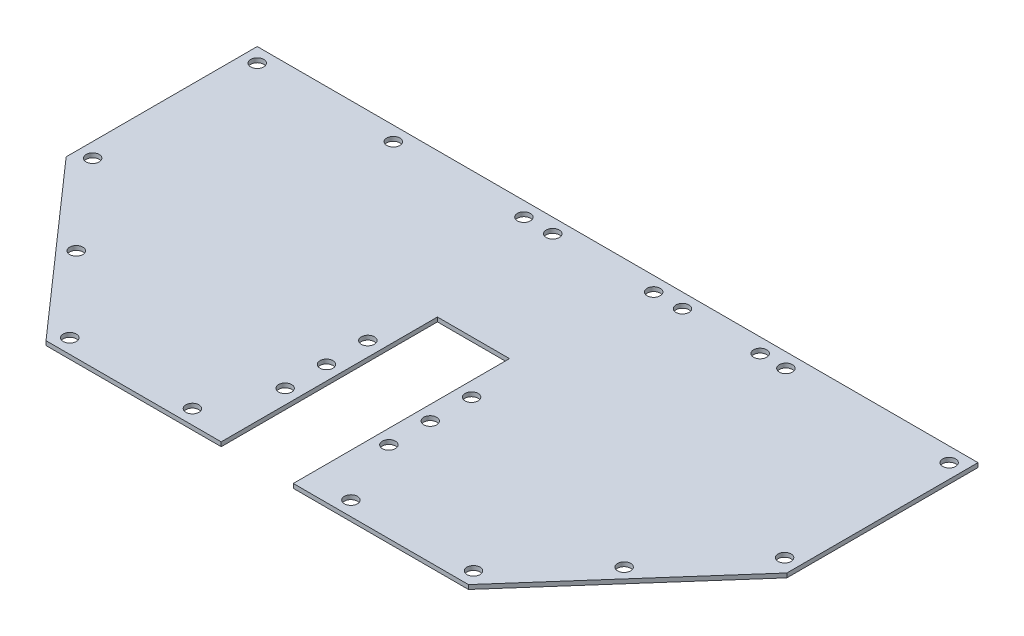
SolidWorks part; units mm, degrees
ref_plane "Front Plane" through (0, 0, 0) normal (0, 0, 1) x (1, 0, 0)
ref_plane "Top Plane" through (0, 0, 0) normal (0, 1, 0) x (1, 0, 0)
ref_plane "Right Plane" through (0, 0, 0) normal (1, 0, 0) x (0, 0, -1)
sketch "Sketch1" plane through (0, 0, 0) normal (0, 1, 0) x (1, 0, 0)
  line L1 (52.5563, -126.9959) -> (114.3, -126.9959)
  line L3 (254, 0) -> (0, 0)
  line L4 (0, 0) -> (0, -67.34)
  line L5 (0, -67.34) -> (52.5563, -126.9959)
  line L6 (254, 0) -> (254, -67.34)
  line L7 (254, -67.34) -> (201.4362, -126.9959)
  line L8 (114.3, -50.8) -> (139.7, -50.8)
  line L9 (139.7, -126.9959) -> (139.7, -50.8)
  line L10 (114.3, -126.9959) -> (114.3, -50.8)
  line L11 (139.7, -126.9959) -> (201.4362, -126.9959)
  circle A0 centre (5.08, -5.08) radius 2.3
  circle A1 centre (53.03, -5.08) radius 2.3
  circle A2 centre (99.06, -5.08) radius 2.3
  circle A3 centre (5.08, -63.08) radius 2.3
  circle A4 centre (99.0662, -121.9159) radius 2.3
  circle A5 centre (55.8562, -121.9159) radius 2.3
  circle A7 centre (182.3, -5.08) radius 2.3
  circle A8 centre (248.92, -5.0864) radius 2.3
  circle A9 centre (248.92, -63.0864) radius 2.3
  circle A10 centre (198.1362, -121.9159) radius 2.3
  circle A11 centre (154.9262, -121.9159) radius 2.3
  circle A13 centre (144.78, -5.08) radius 2.3
  circle A14 centre (109.22, -5.08) radius 2.3
  circle A15 centre (154.94, -5.08) radius 2.3
  circle A16 centre (191.38, -5.08) radius 2.3
  circle A17 centre (223.5281, -94.2391) radius 2.3
  circle A18 centre (144.78, -98.3859) radius 2.3
  circle A19 centre (144.78, -83.8159) radius 2.3
  circle A20 centre (144.78, -69.2459) radius 2.3
  circle A21 centre (109.22, -70.2459) radius 2.3
  circle A22 centre (109.22, -84.8159) radius 2.3
  circle A23 centre (109.22, -99.3859) radius 2.3
  circle A24 centre (30.4664, -94.2371) radius 2.3
  point P6 (52.5563, -126.9959)
  point P8 (201.4362, -126.9959)
  dimension "D3" = 5.08
  dimension "D6" = 47.95
  dimension "D7" = 46.03
  dimension "D8" = 58
  dimension "D9" = 5.08
  dimension "D13" = 43.21
  dimension "D14" = 5.08
  dimension "D15" = 4.6
  dimension "D16" = 4.6
  dimension "D17" = 4.6
  dimension "D18" = 5.08
  dimension "D19" = 4.6
  dimension "D20" = 4.6
  dimension "D21" = 4.6
  dimension "D1" = 67.34
  dimension "D2" = 254
  dimension "D4" = 5.08
  dimension "D5" = 67.34
  dimension "D10" = 22.53
  dimension "D11" = 25.4
  dimension "D12" = 114.3
  dimension "D22" = 10.16
  dimension "D23" = 35.56
  dimension "D24" = 10.16
  dimension "D25" = 27.36
  dimension "D26" = 9.08
  dimension "D27" = 57.54
  dimension "D28" = 58
  dimension "D29" = 5.08
  dimension "D30" = 5.08
  dimension "D31" = 40.19
  dimension "D32" = 5.08
  dimension "D33" = 37.56
  dimension "D34" = 43.21
  dimension "D35" = 5.08
  dimension "D36" = 5.08
  dimension "D37" = 23.53
  dimension "D38" = 5.08
  dimension "D39" = 5.08
  dimension "D40" = 14.57
  dimension "D41" = 14.57
  dimension "D42" = 5.08
  dimension "D43" = 5.08
  dimension "D44" = 14.57
  dimension "D45" = 14.57
  dimension "D46" = 5.08
  dimension "D47" = 5.08
  dimension "D48" = 40.19
  dimension "D49" = 37.56
extrude "Boss-Extrude1" add sketch "Sketch1" along normal blind 1.5
equation "\"Hole Diameter\"= 4.6"
